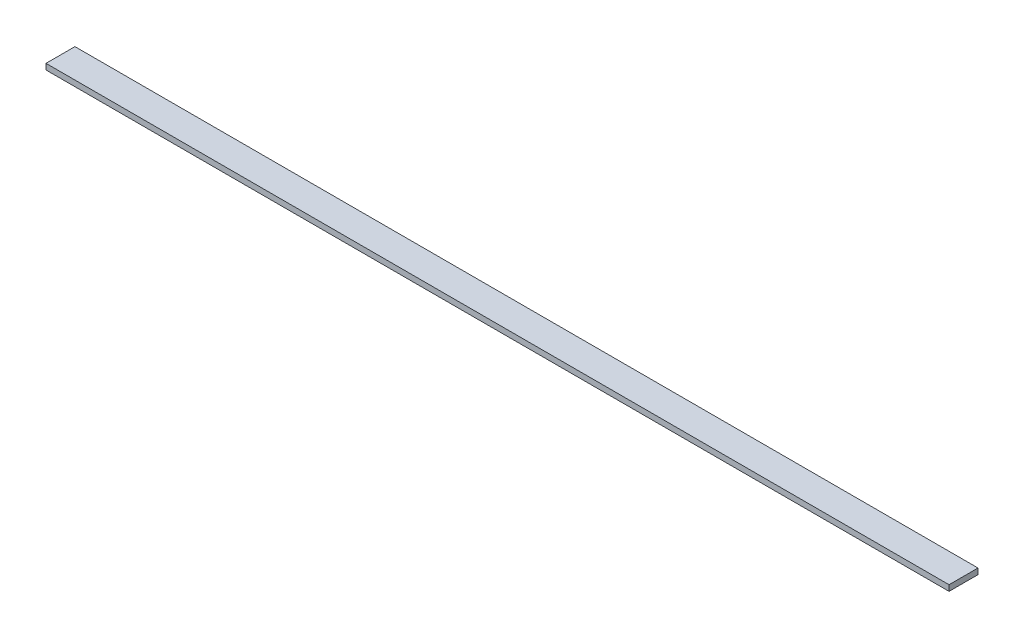
SolidWorks part; units mm, degrees
ref_plane "Front Plane" through (0, 0, 0) normal (0, 0, 1) x (1, 0, 0)
ref_plane "Top Plane" through (0, 0, 0) normal (0, 1, 0) x (1, 0, 0)
ref_plane "Right Plane" through (0, 0, 0) normal (1, 0, 0) x (0, 0, -1)
sketch "Sketch1" plane through (0, 0, 0) normal (0, 1, 0) x (1, 0, 0)
  line L1 (0, 0) -> (312, 0)
  line L2 (0, 0) -> (0, 10)
  line L3 (0, 10) -> (312, 10)
  line L4 (312, 0) -> (312, 10)
  dimension "D1" = 312
  dimension "D2" = 10
extrude "Boss-Extrude1" add sketch "Sketch1" along normal blind 2
